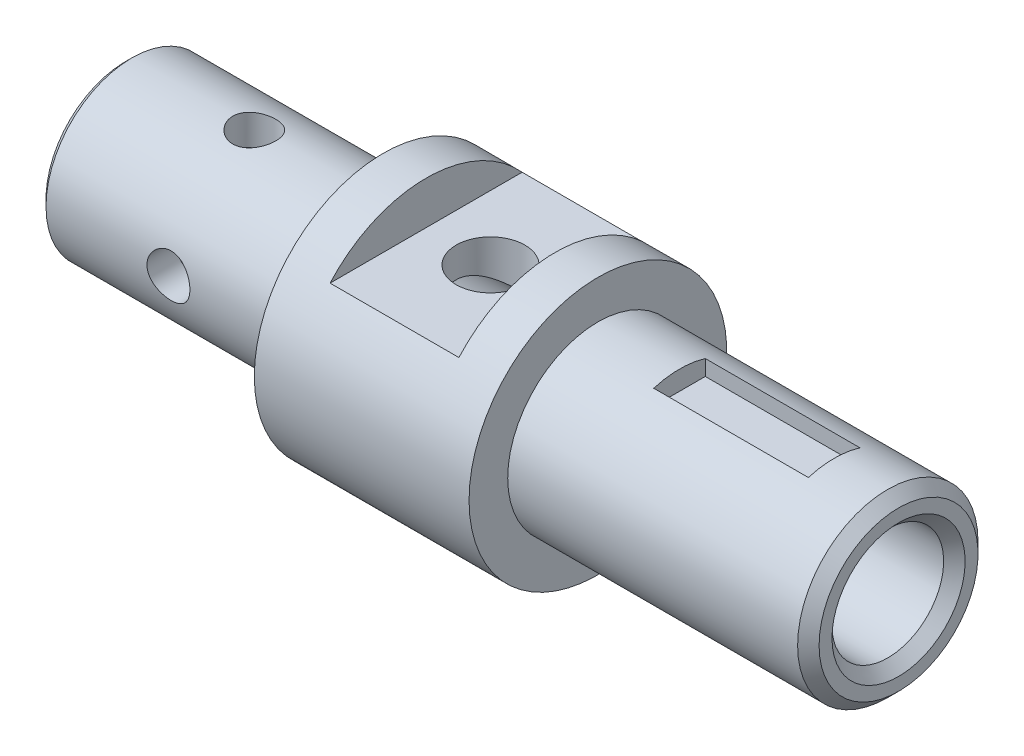
SolidWorks part; units mm, degrees
ref_plane "Спереди" through (0, 0, 0) normal (0, 0, 1) x (1, 0, 0)
ref_plane "Сверху" through (0, 0, 0) normal (0, 1, 0) x (1, 0, 0)
ref_plane "Справа" through (0, 0, 0) normal (1, 0, 0) x (0, 0, -1)
sketch "Эскиз1" plane through (0, 0, 0) normal (0, 0, 1) x (1, 0, 0)
  line L0 (0, 13) -> (180, 13) construction
  line L1 (0, 13) -> (0, 20)
  line L2 (0, 20) -> (60, 20)
  line L3 (60, 20) -> (60, 30)
  line L4 (60, 30) -> (110, 30)
  line L5 (110, 30) -> (110, 21)
  line L6 (110, 21) -> (180, 21)
  line L7 (180, 21) -> (180, 13)
  line L8 (0, 13) -> (180, 13)
  line L9 (0, 0) -> (12.8687, 0) construction
  point P2 (5.79, 13)
  point P6 (0, 0)
  dimension "D1" = 60
  dimension "D2" = 40
  dimension "D3" = 42
  dimension "D4" = 180
  dimension "D5" = 60
  dimension "D6" = 70
  dimension "D7" = 26
revolve "Повернуть1" add sketch "Эскиз1" angle 360 about L9
sketch "Эскиз2" plane through (0, 0, 0) normal (0, 0, 1) x (1, 0, 0)
  line L0 (110, 30) -> (60, 30) construction
  line L1 (70, 30) -> (100, 30)
  line L2 (70, 30) -> (70, 20)
  line L3 (70, 20) -> (100, 20)
  line L4 (100, 30) -> (100, 20)
  line L5 (60, 30) -> (60, -30) construction
  line L6 (60, -30) -> (110, -30) construction
  dimension "D1" = 30
  dimension "D2" = 10
  dimension "D3" = 50
extrude "Вырез-Вытянуть1" cut sketch "Эскиз2" against normal through all both and the other way through all
sketch "Эскиз3" plane through (0, 0, 0) normal (0, 1, 0) x (1, 0, 0)
  line L0 (0, 0) -> (60, 0) construction
  line L1 (60, 30) -> (60, -30) construction
  line L3 (70, 22.3607) -> (100, 22.3607) construction
  circle A0 centre (30, 0) radius 5
  circle A2 centre (85, 0) radius 8
  point P9 (0, 0)
  point P12 (85, 22.3607)
  point P13 (0, 0)
  dimension "D1" = 10
  dimension "D2" = 16
extrude "Вырез-Вытянуть2" cut sketch "Эскиз3" against normal through all both and the other way through all
sketch "Эскиз5" plane through (0, 0, 0) normal (0, 0, 1) x (1, 0, 0)
  line L0 (0, 0) -> (60, 0) construction
  line L1 (0, 20) -> (0, -20) construction
  line L2 (60, 30) -> (60, -30) construction
  circle A0 centre (30, 0) radius 5
  point P8 (35.3176, 0)
  point P9 (16.7647, 0)
  point P10 (30, 0)
  dimension "D1" = 10
extrude "Вырез-Вытянуть3" cut sketch "Эскиз5" against normal through all both and the other way through all
sketch "Эскиз6" plane through (0, 0, 0) normal (0, 0, 1) x (1, 0, 0)
  line L0 (180, 21) -> (110, 21) construction
  line L1 (129, 21) -> (165, 21)
  line L2 (129, 21) -> (129, 16.5)
  line L3 (129, 16.5) -> (165, 16.5)
  line L4 (165, 21) -> (165, 16.5)
  line L5 (180, -21) -> (180, 21) construction
  dimension "D1" = 36
  dimension "D2" = 15
  dimension "D3" = 4.5
extrude "Вырез-Вытянуть4" cut sketch "Эскиз6" against normal mid plane 12
chamfer "Фаска1" distance 1.5 angle 45 2 edges at (0, 0, 13) (0, 0, 20)
chamfer "Фаска2" distance 2.5 angle 45 2 edges at (180, 0, 13) (180, 0, 21)
